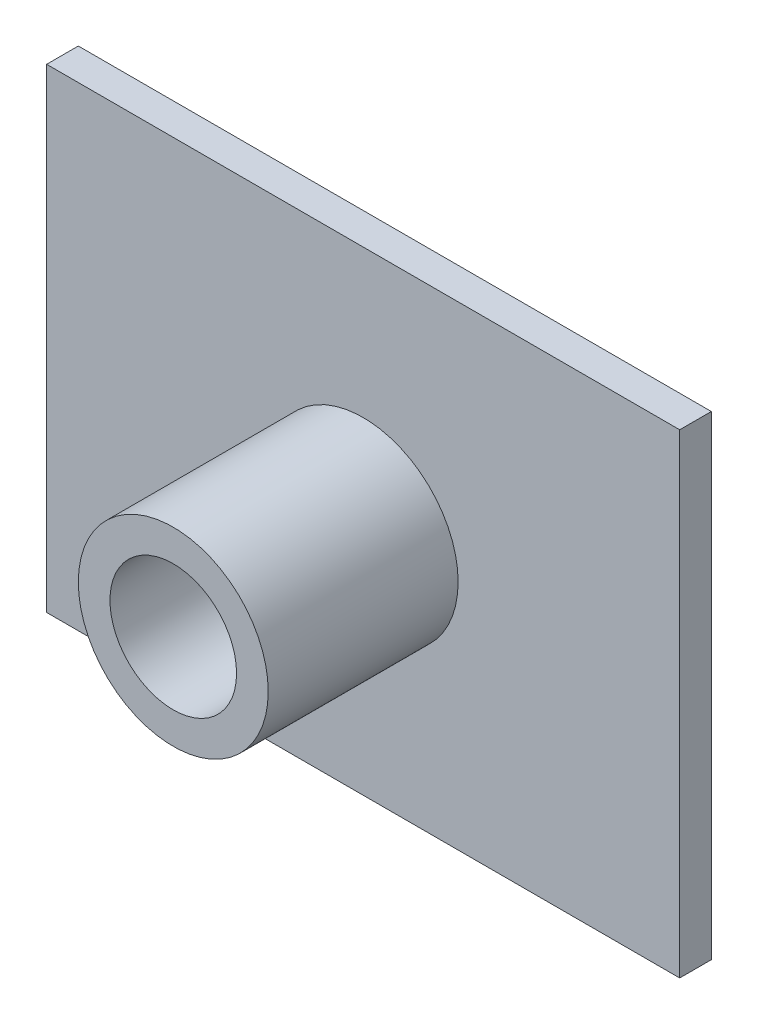
SolidWorks part; units mm, degrees
material "Copper"
ref_plane "Front Plane" through (0, 0, 0) normal (0, 0, 1) x (1, 0, 0)
ref_plane "Top Plane" through (0, 0, 0) normal (0, 1, 0) x (1, 0, 0)
ref_plane "Right Plane" through (0, 0, 0) normal (1, 0, 0) x (0, 0, -1)
sketch "Sketch2" plane through (0, 0, 0) normal (0, 0, 1) x (1, 0, 0)
  line L0 (0, 0) -> (25.4, 0)
  line L1 (0, 0) -> (0, -19.05)
  line L2 (0, -19.05) -> (25.4, -19.05)
  line L3 (25.4, -19.05) -> (25.4, 0)
  dimension "D1" = 19.05
  dimension "D2" = 25.4
extrude "Boss-Extrude1" add sketch "Sketch2" along normal blind 1.27 contours L1 L2 L3 L0
sketch "Sketch3" plane through (0, 0, 1.27) normal (0, 0, 1) x (1, 0, 0)
  circle A0 centre (12.7, -9.7334) radius 3.81
  dimension "D1" = 7.62
extrude "Boss-Extrude2" add sketch "Sketch3" along normal blind 7.62
sketch "Sketch4" plane through (0, 0, 8.89) normal (0, 0, 1) x (1, 0, 0)
  circle A0 centre (12.7, -9.7334) radius 2.54
  dimension "D1" = 5.08
extrude "Cut-Extrude1" cut sketch "Sketch4" against normal blind 7.366
